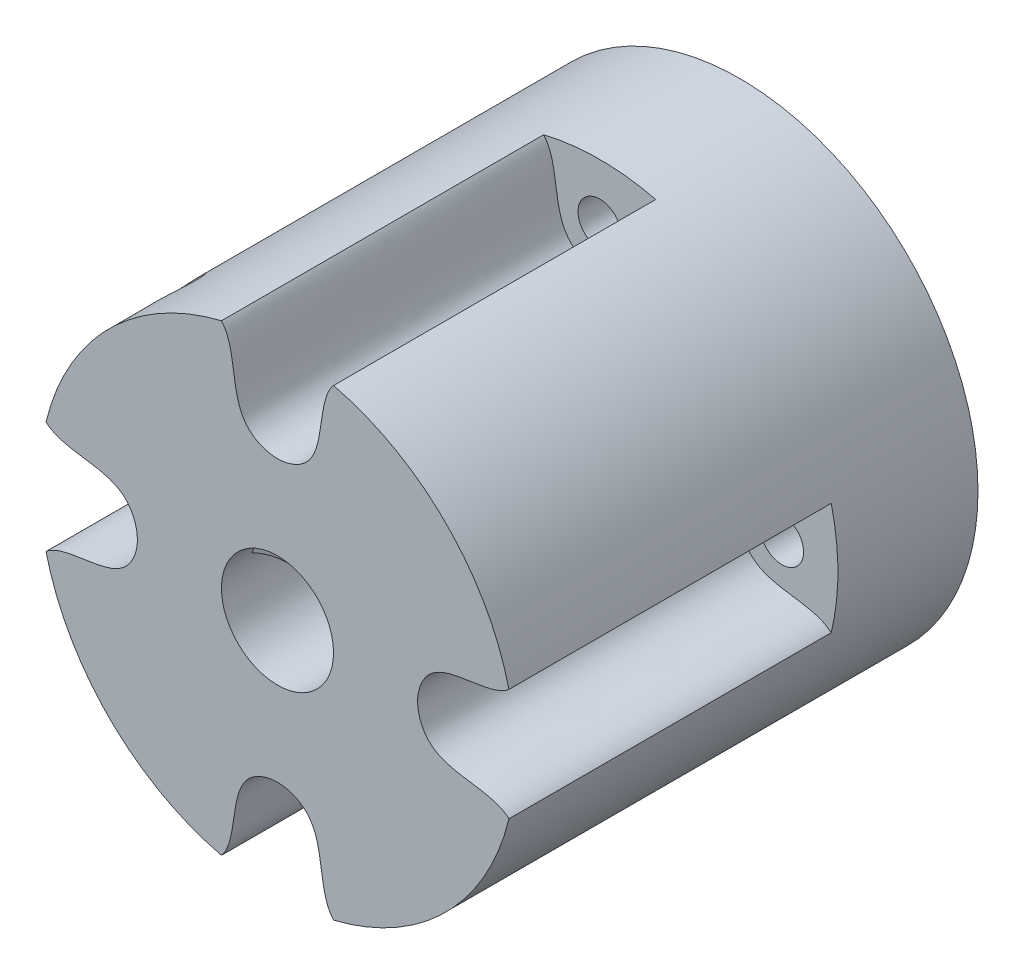
SolidWorks part; units mm, degrees
ref_plane "Front Plane" through (0, 0, 0) normal (0, 0, 1) x (1, 0, 0)
ref_plane "Top Plane" through (0, 0, 0) normal (0, 1, 0) x (1, 0, 0)
ref_plane "Right Plane" through (0, 0, 0) normal (1, 0, 0) x (0, 0, -1)
sketch "Sketch1" plane through (0, 0, 0) normal (0, 0, 1) x (1, 0, 0)
  circle A0 centre (0, 0) radius 17
  dimension "D1" = 34
extrude "Boss-Extrude1" add sketch "Sketch1" along normal blind 10
sketch "Sketch2" plane through (0, 0, 10) normal (0, 0, 1) x (1, 0, 0)
  line L0 (-22.4944, 0) -> (20.7855, 0) construction
  circle A0 centre (0, 0) radius 13 construction
  circle A1 centre (13, 0) radius 1.55
  circle A2 centre (0, -13) radius 1.55
  circle A3 centre (-13, 0) radius 1.55
  circle A4 centre (0, 13) radius 1.55
  point P16 (0, 0)
  dimension "D1" = 26
  dimension "D2" = 3.1
  dimension "D3" = 4
extrude "Cut-Extrude1" cut sketch "Sketch2" against normal through all
sketch "Sketch3" plane through (0, 0, 10) normal (0, 0, 1) x (1, 0, 0)
  line L0 (0, -18.0035) -> (0, 17.5663) construction
  line L1 (-17.924, 0) -> (18.5201, 0) construction
  line L2 (0, 13) -> (3, 10) construction
  line L3 (0, 13) -> (-3.406, 9.594) construction
  circle A0 centre (0, 0) radius 9.5 construction
  arc A1 (16.5227, 4) -> (4, 16.5227) centre (0, 0) ccw
  circle A2 centre (0, 13) radius 3 construction
  circle A3 centre (0, 0) radius 17 construction
  arc A4 (4, -16.5227) -> (16.5227, -4) centre (0, 0) ccw
  arc A5 (-16.5227, -4) -> (-4, -16.5227) centre (0, 0) ccw
  arc A6 (-4, 16.5227) -> (-16.5227, 4) centre (0, 0) ccw
  spline S0 degree 3 poles (4, 16.5227) (2.8162, 15.1791) (3.696, 11.19) (0, 9.669) (-3.696, 11.19) (-2.8162, 15.1791) (-4, 16.5227) knots 0 0 0 0 0.360911 0.5 0.639089 1 1 1 1
  spline S1 degree 3 poles (16.5227, -4) (15.1791, -2.8162) (11.19, -3.696) (9.669, 0) (11.19, 3.696) (15.1791, 2.8162) (16.5227, 4) knots 0 0 0 0 0.360911 0.5 0.639089 1 1 1 1
  spline S2 degree 3 poles (-4, -16.5227) (-2.8162, -15.1791) (-3.696, -11.19) (0, -9.669) (3.696, -11.19) (2.8162, -15.1791) (4, -16.5227) knots 0 0 0 0 0.360911 0.5 0.639089 1 1 1 1
  spline S3 degree 3 poles (-16.5227, 4) (-15.1791, 2.8162) (-11.19, 3.696) (-9.669, 0) (-11.19, -3.696) (-15.1791, -2.8162) (-16.5227, -4) knots 0 0 0 0 0.360911 0.5 0.639089 1 1 1 1
  point P4 (4, 16.5227)
  point P5 (-4, 16.5227)
  point P45 (0, 0)
  point P48 (0, 0)
  dimension "D1" = 19
  dimension "D2" = 6
  dimension "D3" = 4
extrude "Boss-Extrude3" add sketch "Sketch3" along normal blind 23
sketch "Sketch4" plane through (0, 0, 33) normal (0, 0, 1) x (1, 0, 0)
  circle A0 centre (0, 0) radius 4
  dimension "D1" = 8
extrude "Cut-Extrude2" cut sketch "Sketch4" against normal blind 23
ref_plane "Plane1" through (-12.0208, 12.0208, 0) normal (-0.7071, 0.7071, 0) x (0, 0, -1)
sketch "Sketch7" plane through (-12.0208, 12.0208, 0) normal (-0.7071, 0.7071, 0) x (0, 0, -1)
  line L0 (-36.2133, 0) -> (5.8112, 0) construction
  line L1 (-33, 8.8549) -> (-33, -8.8549) construction
  circle A0 centre (-28, 0) radius 1.55
  point P5 (0, 0)
  dimension "D1" = 3.1
  dimension "D2" = 5
extrude "Cut-Extrude3" cut sketch "Sketch7" against normal blind 15
ref_plane "Plane2" through (0, 0, 0) normal (-0.7071, 0.7071, 0) x (0, 0, -1)
sketch "Sketch11" plane through (0, 0, 0) normal (-0.7071, 0.7071, 0) x (0, 0, -1)
  line L1 (-28, 3.5) -> (-31.0311, 1.75)
  line L2 (-31.0311, 1.75) -> (-31.0311, -1.75)
  line L3 (-31.0311, -1.75) -> (-28, -3.5)
  line L4 (-28, -3.5) -> (-24.9689, -1.75)
  line L5 (-24.9689, -1.75) -> (-24.9689, 1.75)
  line L6 (-24.9689, 1.75) -> (-28, 3.5)
  circle A0 centre (-28, 0) radius 3.0311 construction
  dimension "D1" = 3.5
extrude "Cut-Extrude6" cut sketch "Sketch11" along normal blind 7
